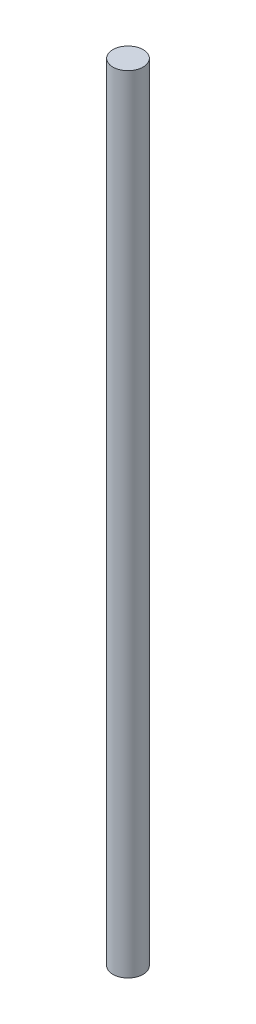
SolidWorks part; units mm, degrees
ref_plane "Front Plane" through (0, 0, 0) normal (0, 0, 1) x (1, 0, 0)
ref_plane "Top Plane" through (0, 0, 0) normal (0, 1, 0) x (1, 0, 0)
ref_plane "Right Plane" through (0, 0, 0) normal (1, 0, 0) x (0, 0, -1)
sketch "Sketch1" plane through (0, 0, 0) normal (0, 1, 0) x (1, 0, 0)
  circle A0 centre (0, 0) radius 12.7
  dimension "D1" = 25.4
sketch "Sketch2" plane through (0, 0, 0) normal (0, 1, 0) x (1, 0, 0)
  circle A0 centre (0, 0) radius 10.795
  dimension "D1" = 21.59
sketch "Sketch3" plane through (0, 0, 0) normal (1, 0, 0) x (0, 0, -1)
  line L0 (12.7, 0) -> (-12.7, 0) construction
  line L1 (-13.6481, -2.54) -> (11.7912, -2.54)
  line L2 (-13.6481, -2.54) -> (-13.6481, -10.16)
  line L3 (-13.6481, -10.16) -> (11.7912, -10.16)
  line L4 (11.7912, -2.54) -> (11.7912, -10.16)
  dimension "D1" = 2.54
  dimension "D2" = 7.62
  dimension "D3" = 25.4393
sketch "Sketch5" plane through (0, 0, 0) normal (0, 1, 0) x (1, 0, 0)
  line L0 (0, 0) -> (8.636, 0) construction
  line L1 (0, 0) -> (-4.318, -7.479) construction
  circle A0 centre (8.636, 0) radius 1.27
  circle A1 centre (-4.318, -7.479) radius 1.27
  circle A2 centre (-4.318, 7.479) radius 1.27
  dimension "D1" = 2.54
  dimension "D2" = 8.636
  dimension "D4" = 120
  dimension "D3" = 3
sketch "Sketch8" plane through (0, 0, 0) normal (0, 1, 0) x (1, 0, 0)
  circle A0 centre (0, 0) radius 1.27
  dimension "D1" = 2.54
extrude "Boss-Extrude2" add sketch "Sketch8" along normal blind 66.04
equation "\"D1@Sketch7\" = \"D1@Sketch1\" / 10"
equation "\"D2@Sketch7\" = ( \"D1@Sketch1\" / 2 ) - ( \"D1@Sketch7\" * 1.6 )"
equation "\"D1@Sketch2\" = \"D1@Sketch1\" * 0.85"
equation "\"D2@Sketch3\" = \"D1@Boss\" - \"Extrude1\" * 3 / 5"
equation "\"D1@Sketch3\" = \"D1@Boss\" - \"Extrude1\" / 5"
equation "\"D1@Sketch5\" = ( \"D1@Sketch1\" / 10 )"
equation "\"D2@Sketch5\" = ( \"D1@Sketch1\" / 2 ) - ( \"D1@Sketch5\" * 1.6 )"
equation "\"D1@Sketch8\" = \"D1@Sketch1\" / 10"
